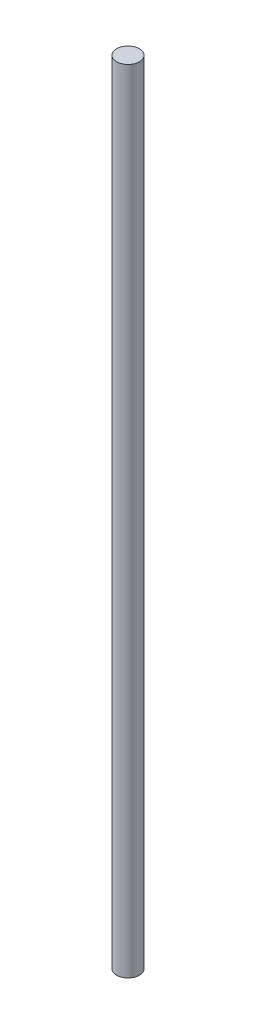
SolidWorks part; units mm, degrees
ref_plane "Front Plane" through (0, 0, 0) normal (0, 0, 1) x (1, 0, 0)
ref_plane "Top Plane" through (0, 0, 0) normal (0, 1, 0) x (1, 0, 0)
ref_plane "Right Plane" through (0, 0, 0) normal (1, 0, 0) x (0, 0, -1)
sketch "Sketch1" plane through (0, 0, 0) normal (0, 1, 0) x (1, 0, 0)
  circle A0 centre (0, 0) radius 34.925
  dimension "D1" = 69.85
extrude "Boss-Extrude1" add sketch "Sketch1" along normal blind 2438.4
